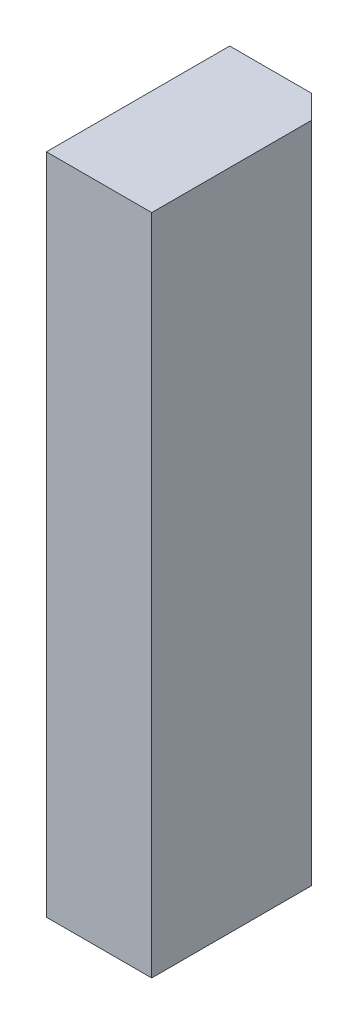
SolidWorks part; units mm, degrees
ref_plane "前基準面" through (0, 0, 0) normal (0, 0, 1) x (1, 0, 0)
ref_plane "上基準面" through (0, 0, 0) normal (0, 1, 0) x (1, 0, 0)
ref_plane "右基準面" through (0, 0, 0) normal (1, 0, 0) x (0, 0, -1)
sketch "草圖1" plane through (0, 0, 0) normal (0, 1, 0) x (1, 0, 0)
  line L1 (-1.35, 2.35) -> (1.35, 2.35)
  line L2 (-1.35, 2.35) -> (-1.35, -2.35)
  line L3 (-1.35, -2.35) -> (1.35, -2.35)
  line L4 (1.35, 2.35) -> (1.35, -2.35)
  line L5 (-1.35, 2.35) -> (1.35, -2.35) construction
  line L6 (-1.35, -2.35) -> (1.35, 2.35) construction
  point P0 (0, 0)
  dimension "D1" = 2.7
  dimension "D2" = 4.7
extrude "伸長1" add sketch "草圖1" along normal blind 17
chamfer "導角1" distance 0.6 angle 45 1 edges at (1.35, 8.5, -2.35)
sketch "草圖3" plane through (-1.35, 0, 0) normal (-1, 0, 0) x (0, 0, 1)
  line L0 (-2.45, 0) -> (-2.45, 1) construction
  line L1 (-2.35, 0) -> (2.35, 0) construction
  line L2 (2.35, 17) -> (2.35, 0) construction
  circle A0 centre (-2.45, 1) radius 0.5
  dimension "D2" = 1
  dimension "D1" = 4.8
  dimension "D3" = 1
extrude "伸長2" cut sketch "草圖3" against normal up to next
